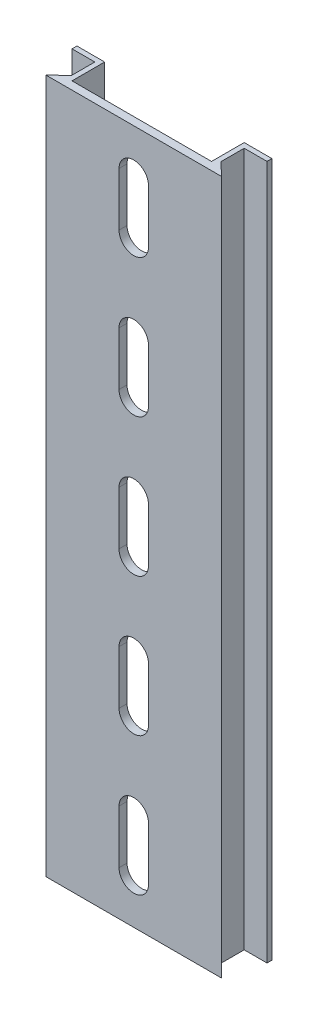
SolidWorks part; units mm, degrees
ref_plane "Front Plane" through (0, 0, 0) normal (0, 0, 1) x (1, 0, 0)
ref_plane "Top Plane" through (0, 0, 0) normal (0, 1, 0) x (1, 0, 0)
ref_plane "Right Plane" through (0, 0, 0) normal (1, 0, 0) x (0, 0, -1)
sketch "Sketch1" plane through (0, 0, 0) normal (0, 1, 0) x (1, 0, 0)
  line L0 (0, 0) -> (0, 1.4478)
  line L1 (-12.6365, 1.4478) -> (12.6365, 1.4478)
  line L2 (12.6365, 1.4478) -> (12.6365, 7.366)
  line L3 (12.6365, 7.366) -> (17.653, 7.366)
  line L4 (17.653, 7.366) -> (17.653, 6.477)
  line L5 (17.653, 6.477) -> (13.5255, 6.477)
  line L6 (13.5255, 6.477) -> (13.5255, 2.286)
  line L7 (13.5255, 2.286) -> (15.875, 0)
  line L8 (15.875, 0) -> (-15.875, 0)
  line L9 (-13.5255, 2.286) -> (-15.875, 0)
  line L10 (-13.5255, 6.477) -> (-13.5255, 2.286)
  line L11 (-17.653, 6.477) -> (-13.5255, 6.477)
  line L12 (-17.653, 7.366) -> (-17.653, 6.477)
  line L13 (-12.6365, 7.366) -> (-17.653, 7.366)
  line L14 (-12.6365, 1.4478) -> (-12.6365, 7.366)
  dimension "D1" = 15.875
  dimension "D2" = 13.5255
  dimension "D3" = 0.889
  dimension "D4" = 1.4478
  dimension "D5" = 7.366
  dimension "D6" = 0.889
  dimension "D7" = 2.286
  dimension "D8" = 17.653
extrude "Boss-Extrude1" add sketch "Sketch1" along normal mid plane 125.73 contours L1 L14 L13 L12 L11 L10 L9 L8 L0 | L8 L7 L6 L5 L4 L3 L2 L1 L0
sketch "Sketch2" plane through (0, 0, 0) normal (0, 0, 1) x (1, 0, 0)
  line L0 (0, -4.833) -> (0, 4.833) construction
  line L1 (-2.667, -4.833) -> (-2.667, 4.833)
  line L2 (2.667, -4.833) -> (2.667, 4.833)
  line L3 (-15.875, 0) -> (15.875, 0) construction
  line L4 (-15.875, 62.865) -> (-15.875, -62.865) construction
  line L5 (15.875, 62.865) -> (15.875, -62.865) construction
  line L6 (0, 62.865) -> (0, -62.865) construction
  line L7 (15.875, 62.865) -> (-15.875, 62.865) construction
  line L8 (15.875, -62.865) -> (-15.875, -62.865) construction
  line L9 (0, 20.167) -> (0, 29.833) construction
  line L10 (-2.667, 20.167) -> (-2.667, 29.833)
  line L11 (2.667, 20.167) -> (2.667, 29.833)
  line L12 (0, 45.167) -> (0, 54.833) construction
  line L13 (-2.667, 45.167) -> (-2.667, 54.833)
  line L14 (2.667, 45.167) -> (2.667, 54.833)
  line L15 (0, -29.833) -> (0, -20.167) construction
  line L16 (-2.667, -29.833) -> (-2.667, -20.167)
  line L17 (2.667, -29.833) -> (2.667, -20.167)
  line L18 (0, -54.833) -> (0, -45.167) construction
  line L19 (-2.667, -54.833) -> (-2.667, -45.167)
  line L20 (2.667, -54.833) -> (2.667, -45.167)
  arc A0 (-2.667, -4.833) -> (2.667, -4.833) centre (0, -4.833) ccw
  arc A1 (2.667, 4.833) -> (-2.667, 4.833) centre (0, 4.833) ccw
  arc A2 (-2.667, 20.167) -> (2.667, 20.167) centre (0, 20.167) ccw
  arc A3 (2.667, 29.833) -> (-2.667, 29.833) centre (0, 29.833) ccw
  arc A4 (-2.667, 45.167) -> (2.667, 45.167) centre (0, 45.167) ccw
  arc A5 (2.667, 54.833) -> (-2.667, 54.833) centre (0, 54.833) ccw
  arc A6 (-2.667, -29.833) -> (2.667, -29.833) centre (0, -29.833) ccw
  arc A7 (2.667, -20.167) -> (-2.667, -20.167) centre (0, -20.167) ccw
  arc A8 (-2.667, -54.833) -> (2.667, -54.833) centre (0, -54.833) ccw
  arc A9 (2.667, -45.167) -> (-2.667, -45.167) centre (0, -45.167) ccw
  point P3 (0, 0)
  point P15 (0, -7.5)
  point P16 (0, 7.5)
  point P26 (0, 25)
  point P33 (0, 50)
  point P39 (0, -25)
  point P46 (0, -50)
  dimension "D1" = 15
  dimension "D2" = 2.667
  dimension "D3" = 3
  dimension "D4" = 3
extrude "Cut-Extrude1" cut sketch "Sketch2" against normal through all
